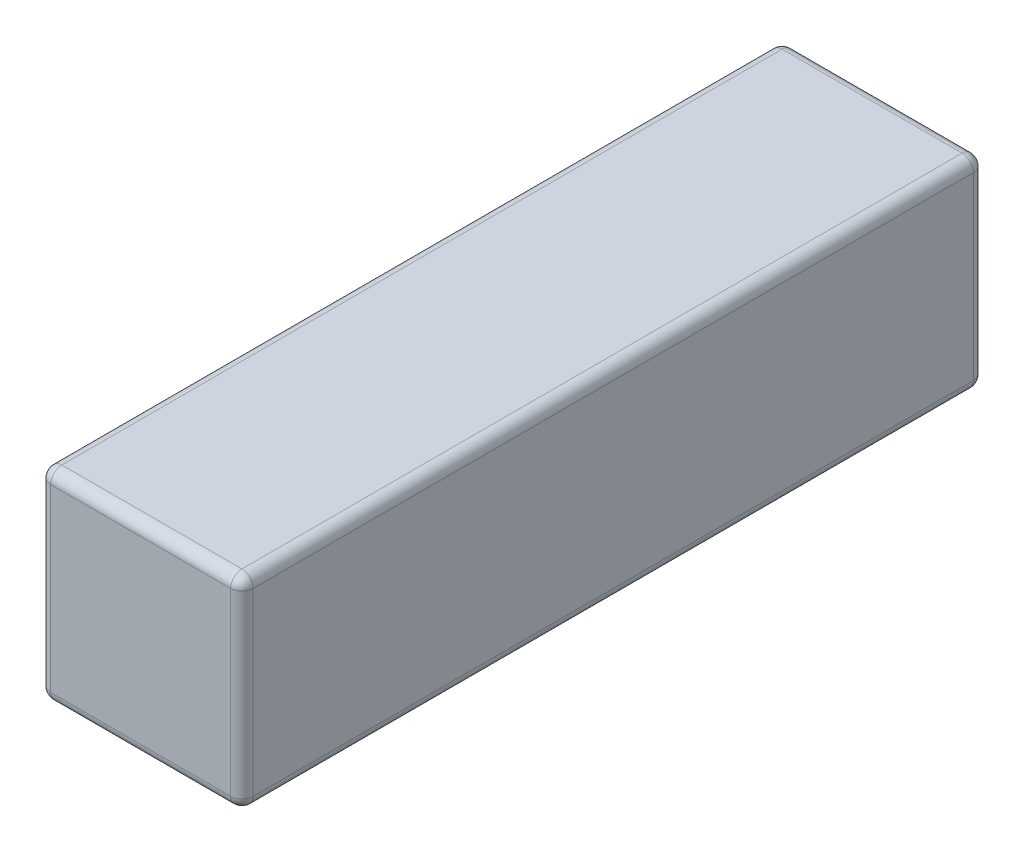
SolidWorks part; units mm, degrees
ref_plane "Front Plane" through (0, 0, 0) normal (0, 0, 1) x (1, 0, 0)
ref_plane "Top Plane" through (0, 0, 0) normal (0, 1, 0) x (1, 0, 0)
ref_plane "Right Plane" through (0, 0, 0) normal (1, 0, 0) x (0, 0, -1)
sketch "Sketch1" plane through (0, 0, 0) normal (0, 0, 1) x (1, 0, 0)
  line L1 (4.5, 4.5) -> (-4.5, 4.5)
  line L2 (4.5, 4.5) -> (4.5, -4.5)
  line L3 (4.5, -4.5) -> (-4.5, -4.5)
  line L4 (-4.5, 4.5) -> (-4.5, -4.5)
  line L5 (4.5, 4.5) -> (-4.5, -4.5) construction
  line L6 (4.5, -4.5) -> (-4.5, 4.5) construction
  point P0 (0, 0)
  dimension "D1" = 9
  dimension "D2" = 9
extrude "Boss-Extrude1" add sketch "Sketch1" along normal blind 33
fillet "Fillet1" radius 0.5 12 edges at (-4.5, 4.5, 16.5) (-4.5, -4.5, 16.5) (4.5, -4.5, 16.5) (4.5, 4.5, 16.5) (0, 4.5, 0) (4.5, 0, 0) (0, -4.5, 0) (-4.5, 0, 0) (-4.5, 0, 33) (0, -4.5, 33) (4.5, 0, 33) (0, 4.5, 33)
